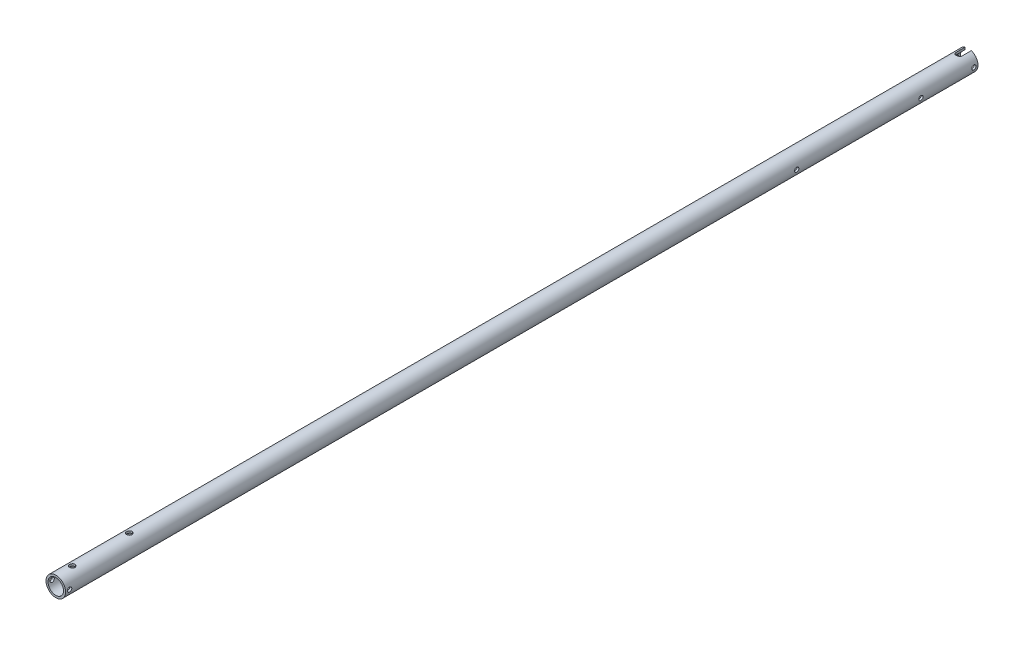
SolidWorks part; units mm, degrees
material "6061-T6 (SS)"
ref_plane "Front" through (0, 0, 0) normal (0, 0, 1) x (1, 0, 0)
ref_plane "Top" through (0, 0, 0) normal (0, 1, 0) x (1, 0, 0)
ref_plane "Right" through (0, 0, 0) normal (1, 0, 0) x (0, 0, -1)
sketch "Sketch1" plane through (0, 0, 0) normal (0, 0, 1) x (1, 0, 0)
  circle A0 centre (0, 0) radius 15.24
  circle A1 centre (0, 0) radius 12.065
  dimension "D1" = 3.175
  dimension "D2" = 30.48
extrude "Boss-Extrude1" add sketch "Sketch1" along normal blind 1422.4
ref_plane "Plane1" through (0, -15.24, 0) normal (0, -1, 0) x (-1, 0, 0)
sketch "Sketch2" plane through (0, -15.24, 0) normal (0, 1, 0) x (1, 0, 0)
  line L0 (0, 0) -> (0, -180.975) construction
  line L1 (0, -180.975) -> (0, -1308.1) construction
  line L2 (0, -1308.1) -> (0, -1397) construction
  line L3 (-15.24, -1422.4) -> (15.24, -1422.4) construction
  point P3 (0, -88.9)
  point P8 (0, -282.575)
  point P9 (0, -6.35)
  dimension "D1" = 180.975
  dimension "D2" = 88.9
  dimension "D3" = 88.9
  dimension "D4" = 25.4
  dimension "D5" = 101.6
  dimension "D6" = 6.35
hole_wizard "1/4 Clearance Hole2" positions "Sketch6" profile "Sketch5" hole size "1/4" standard "ANSI Inch"
sketch "Sketch6" plane through (0, -15.24, 0) normal (0, -1, 0) x (-1, 0, 0)
  point P8 (0, -282.575)
  point P20 (0, -180.975)
  point P23 (0, -88.9)
sketch "Sketch5" plane through (0, -15.24, 282.575) normal (1, 0, 0) x (0, 0, -1)
  line L0 (0, 0) -> (0, 30.48)
  line L1 (0, 30.48) -> (3.3782, 30.48)
  line L2 (3.3782, 30.48) -> (3.3782, 0)
  line L5 (3.3782, 0) -> (0, 0)
  line L11 (0, -6.35) -> (0, 107.95) construction
  dimension "Thru Hole Dia." = 6.7564
  dimension "Thru Hole Depth" = 30.48
hole_wizard "5/16 Clearance Hole1" positions "Sketch8" profile "Sketch7" hole size "5/16" standard "ANSI Inch" end condition through all
sketch "Sketch8" plane through (0, -15.24, 0) normal (0, -1, 0) x (-1, 0, 0)
  point P0 (0, -1397)
  point P3 (0, -1308.1)
sketch "Sketch7" plane through (0, -15.24, 1397) normal (1, 0, 0) x (0, 0, -1)
  line L0 (0, 0) -> (0, 30.48)
  line L1 (0, 30.48) -> (4.2164, 30.48)
  line L2 (4.2164, 30.48) -> (4.2164, 0)
  line L5 (4.2164, 0) -> (0, 0)
  line L11 (0, -6.35) -> (0, 107.95) construction
  dimension "Thru Hole Dia." = 8.4328
  dimension "Thru Hole Depth" = 30.48
ref_plane "Plane2" through (-15.24, 0, 0) normal (-1, 0, 0) x (0, 0, 1)
sketch "Sketch9" plane through (-15.24, 0, 0) normal (-1, 0, 0) x (0, 0, 1)
  line L0 (0, 0) -> (88.9, 0) construction
  line L1 (88.9, 0) -> (282.575, 0) construction
  line L2 (1416.05, 0) -> (1422.4, 0) construction
  line L3 (1422.4, -15.24) -> (1422.4, 15.24) construction
  point P3 (6.35, 0)
  dimension "D1" = 88.9
  dimension "D2" = 193.675
  dimension "D3" = 6.35
  dimension "D4" = 6.35
hole_wizard "1/4 Clearance Hole3" positions "Sketch11" profile "Sketch10" hole size "1/4" standard "ANSI Inch" end condition through all
sketch "Sketch11" plane through (-15.24, 0, 0) normal (-1, 0, 0) x (0, 0, 1)
  point P0 (88.9, 0)
  point P3 (282.575, 0)
  point P7 (6.35, 0)
  point P10 (1416.05, 0)
sketch "Sketch10" plane through (-15.24, 0, 88.9) normal (0, 1, 0) x (0, 0, 1)
  line L0 (0, 0) -> (0, 30.48)
  line L1 (0, 30.48) -> (3.3782, 30.48)
  line L2 (3.3782, 30.48) -> (3.3782, 0)
  line L5 (3.3782, 0) -> (0, 0)
  line L11 (0, -6.35) -> (0, 107.95) construction
  dimension "Thru Hole Dia." = 6.7564
  dimension "Thru Hole Depth" = 30.48
sketch "Sketch12" plane through (0, -15.24, 0) normal (0, -1, 0) x (-1, 0, 0)
  line L0 (0, 0) -> (4.7625, 0)
  line L1 (4.7625, 0) -> (4.7625, -14.2875)
  line L2 (-4.7625, -14.2875) -> (-4.7625, 0)
  line L3 (-4.7625, 0) -> (0, 0)
  arc A0 (4.7625, -14.2875) -> (-4.7625, -14.2875) centre (0, -14.2875) cw
  dimension "D1" = 9.525
  dimension "D2" = 14.2875
extrude "Cut-Extrude1" cut sketch "Sketch12" against normal through all
